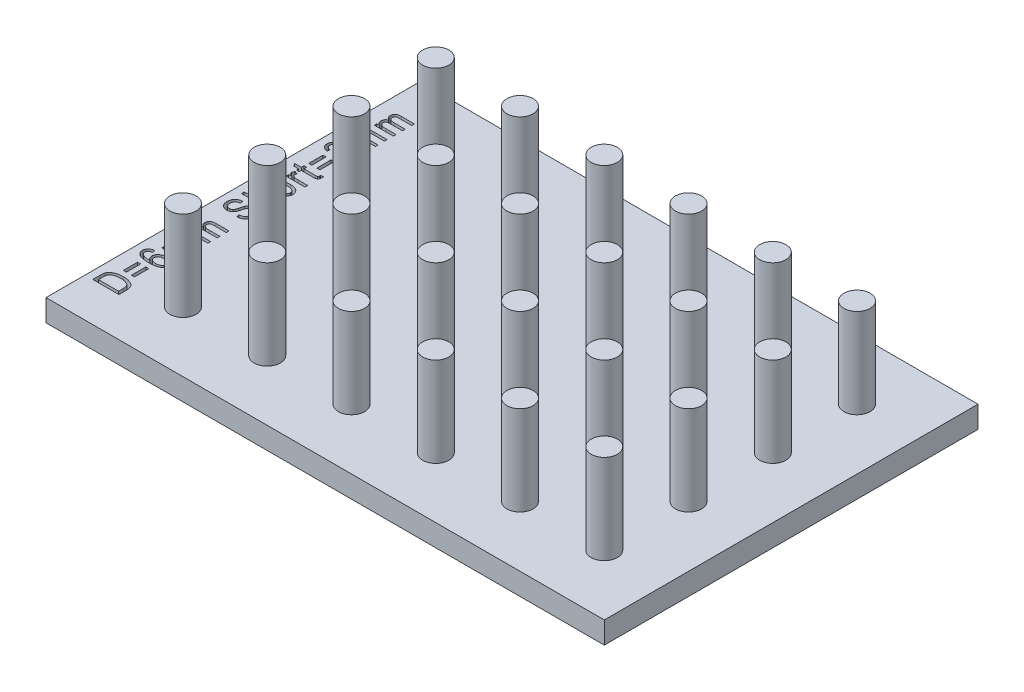
SolidWorks part; units mm, degrees
material "PVC Rigid"
ref_plane "Front Plane" through (0, 0, 0) normal (0, 0, 1) x (1, 0, 0)
ref_plane "Top Plane" through (0, 0, 0) normal (0, 1, 0) x (1, 0, 0)
ref_plane "Right Plane" through (0, 0, 0) normal (1, 0, 0) x (0, 0, -1)
ref_plane "Top of 24 well plate" through (0, 6, 0) normal (0, 1, 0) x (1, 0, 0)
ref_plane "Bottom of 24 well plate" through (0, 23.5, 0) normal (0, 1, 0) x (1, 0, 0)
sketch "Sketch1" plane through (0, 0, 0) normal (0, 1, 0) x (1, 0, 0)
  line L1 (-63.945, 42.8) -> (63.945, 42.8)
  line L2 (-63.945, 42.8) -> (-63.945, -42.8)
  line L3 (-63.945, -42.8) -> (63.945, -42.8)
  line L4 (63.945, 42.8) -> (63.945, -42.8)
  line L5 (-63.945, 42.8) -> (63.945, -42.8) construction
  line L6 (-63.945, -42.8) -> (63.945, 42.8) construction
  point P0 (0, 0)
  dimension "D1" = 127.89
  dimension "D2" = 85.6
ref_plane "Middle of 24 well plate" through (0, 14.75, 0) normal (0, 1, 0) x (1, 0, 0)
sketch "Wells_LSP" plane through (0, 0, 0) normal (0, 1, 0) x (1, 0, 0)
  line L0 (-46.425, 28.96) -> (-27.125, 28.96) construction
  line L1 (-63.945, 42.8) -> (63.945, 42.8) construction
  line L2 (-63.945, 42.8) -> (-63.945, -42.8) construction
  circle A0 centre (-46.425, 28.96) radius 7.81
  circle A1 centre (-27.125, 28.96) radius 7.81
  circle A2 centre (-7.825, 28.96) radius 7.81
  circle A3 centre (11.475, 28.96) radius 7.81
  circle A4 centre (30.775, 28.96) radius 7.81
  circle A5 centre (50.075, 28.96) radius 7.81
  circle A6 centre (-27.125, 9.66) radius 7.81
  circle A7 centre (-7.825, 9.66) radius 7.81
  circle A8 centre (11.475, 9.66) radius 7.81
  circle A9 centre (30.775, 9.66) radius 7.81
  circle A10 centre (50.075, 9.66) radius 7.81
  circle A11 centre (-27.125, -9.64) radius 7.81
  circle A12 centre (-7.825, -9.64) radius 7.81
  circle A13 centre (11.475, -9.64) radius 7.81
  circle A14 centre (30.775, -9.64) radius 7.81
  circle A15 centre (50.075, -9.64) radius 7.81
  circle A16 centre (-27.125, -28.94) radius 7.81
  circle A17 centre (-7.825, -28.94) radius 7.81
  circle A18 centre (11.475, -28.94) radius 7.81
  circle A19 centre (30.775, -28.94) radius 7.81
  circle A20 centre (50.075, -28.94) radius 7.81
  circle A21 centre (-46.425, 9.66) radius 7.81
  circle A22 centre (-46.425, -9.64) radius 7.81
  circle A23 centre (-46.425, -28.94) radius 7.81
  dimension "D2" = 6
  dimension "D4" = 4
  dimension "D7" = 15.62
  dimension "D3" = 19.3
  dimension "D5" = 13.84
  dimension "D6" = 17.52
ref_plane "Plane1" through (0, 0, -28.96) normal (0, 0, 1) x (1, 0, 0)
sketch "Sketch2" plane through (0, 0, -28.96) normal (0, 0, 1) x (1, 0, 0)
  line L0 (50.075, 14.75) -> (50.075, 0) construction
  line L1 (50.075, 20.5) -> (53.075, 20.5)
  line L2 (50.075, 20.5) -> (50.075, 0)
  line L3 (50.075, 0) -> (53.075, 0)
  line L4 (53.075, 20.5) -> (53.075, 0)
  line L5 (55, 6) -> (-55, 6) construction
  line L8 (55, 14.75) -> (-55, 14.75) construction
  line L9 (55, 23.5) -> (-55, 23.5) construction
  line L10 (-63.945, 0) -> (63.945, 0) construction
  point P10 (53.075, 6)
  point P13 (50.075, 14.75)
  dimension "D1" = 0
  dimension "D2" = 3
  dimension "D3" = 3
revolve "Revolve1" add sketch "Sketch2" angle 360 about L2
extrude "Boss-Extrude2" add sketch "Sketch1" against normal blind 5
pattern_linear "LPattern2" count 4 spacing 19.3 along (0, 0, 1) count 6 spacing 19.3 along (-1, 0, 0) of "Revolve1"
sketch "Sketch5" plane through (0, 0, 0) normal (0, 1, 0) x (1, 0, 0)
  line L0 (-56.1948, 42.8) -> (-56.1948, -42.8) construction
  line L1 (63.945, 42.8) -> (-63.945, 42.8) construction
  line L2 (-63.945, -42.8) -> (63.945, -42.8) construction
  text T0 "D=6mm Short=3mm\r\n" font "Arial Narrow" height 6
extrude "Cut-Extrude1" cut sketch "Sketch5" against normal blind 2
equation "\"D1\"= 0.32"
equation "\"D1\"= 1.27 - 0.32"
